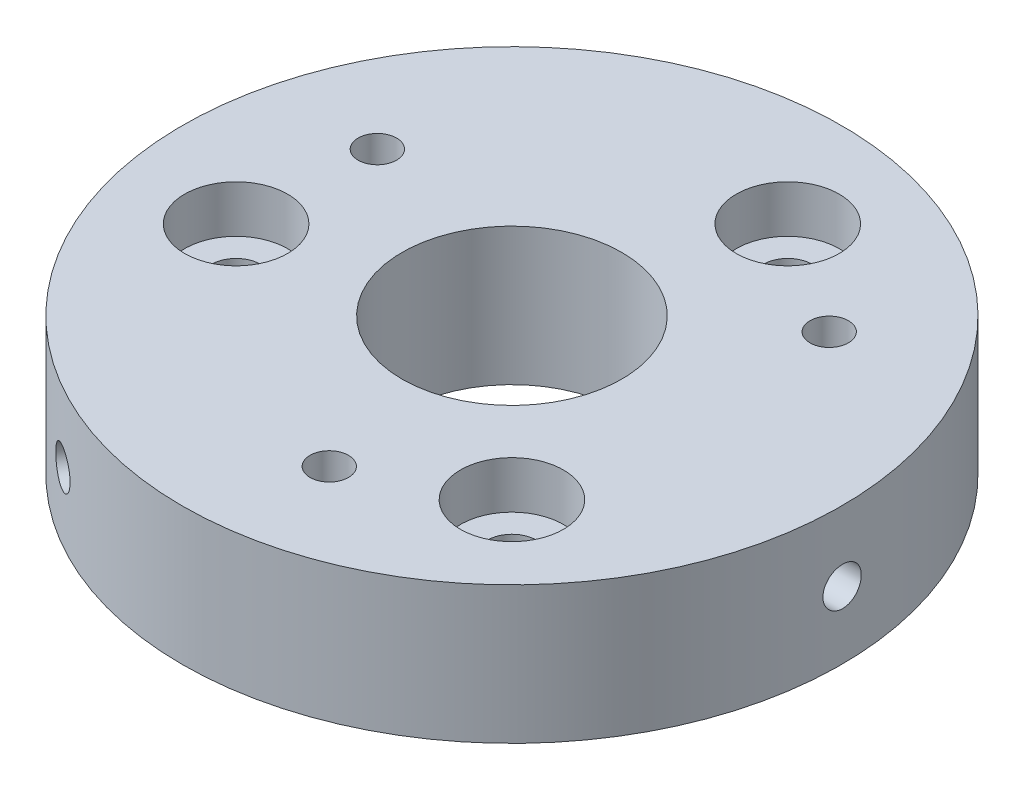
SolidWorks part; units mm, degrees
ref_plane "Front Plane" through (0, 0, 0) normal (0, 0, 1) x (1, 0, 0)
ref_plane "Top Plane" through (0, 0, 0) normal (0, 1, 0) x (1, 0, 0)
ref_plane "Right Plane" through (0, 0, 0) normal (1, 0, 0) x (0, 0, -1)
sketch "Sketch1" plane through (0, 0, 0) normal (0, 1, 0) x (1, 0, 0)
  circle A0 centre (0, 0) radius 15.24
  dimension "D1" = 30.48
extrude "Boss-Extrude1" add sketch "Sketch1" along normal blind 6.35
hole_wizard "CBORE for #2 Socket Head Cap Screw1" positions "Sketch3" profile "Sketch4" counterbore size "#2" standard "ANSI Inch" end condition through all
sketch "Sketch3" plane through (0, 6.35, 0) normal (0, 1, 0) x (1, 0, 0)
  line L3 (0, 0) -> (7.3638, -7.3638)
  point P0 (7.3638, -7.3638)
sketch "Sketch4" plane through (7.3638, 6.35, 7.3638) normal (1, 0, 0) x (0, 0, 1)
  line L0 (0, 0) -> (0, 6.35)
  line L1 (0, 6.35) -> (1.1303, 6.35)
  line L3 (1.1303, 6.35) -> (1.1303, 2.1844)
  line L4 (1.1303, 2.1844) -> (2.3812, 2.1844)
  line L5 (2.3812, 2.1844) -> (2.3812, 0)
  line L7 (2.3812, 0) -> (0, 0)
  line L11 (0, -6.35) -> (0, 107.95) construction
  dimension "Thru Hole Dia." = 2.2606
  dimension "Thru Hole Depth" = 6.35
  dimension "C'Bore Dia." = 4.7625
  dimension "C'Bore Depth" = 2.1844
pattern_circular "CirPattern1" count 3 over 360 about axis through (0, 0, 0) along (0, 1, 0) of "CBORE for #2 Socket Head Cap Screw1"
sketch "Sketch9" plane through (0, 6.35, 0) normal (0, 1, 0) x (1, 0, 0)
  line L0 (0, 0) -> (7.9776, 6.694)
  circle A0 centre (7.9776, 6.694) radius 1.4122
hole_wizard "Tap Drill for #2-56 Tap2" positions "3DSketch1" profile "Sketch10" hole size "#2-56" standard "ANSI Inch"
sketch3d "3DSketch1"
  point P0 (7.9776, 6.35, -6.694)
sketch "Sketch10" plane through (7.9776, 6.35, -6.694) normal (1, 0, 0) x (0, 0, 1)
  line L0 (0, 0) -> (0, 4.5982)
  line L1 (0, 4.5982) -> (0.889, 4.064)
  line L2 (0.889, 4.064) -> (0.889, 0)
  line L5 (0.889, 0) -> (0, 0)
  line L10 (0, 4.5982) -> (-0.889, 4.064) construction
  line L11 (0, -6.35) -> (0, 107.95) construction
  dimension "Hole Dia." = 1.778
  dimension "Hole Depth" = 4.064
  dimension "Drill Angle" = 118
pattern_circular "CirPattern2" count 3 every 120 about axis through (0, 0, 0) along (0, 1, 0) of "Tap Drill for #2-56 Tap2"
ref_plane "Plane1" [suppressed] through (0, 3.175, 0) normal (0, 1, 0) x (1, 0, 0)
sketch "Sketch11" [suppressed] plane through (0, 3.175, 0) normal (0, 1, 0) x (1, 0, 0)
  line L0 (0, 0) -> (-7.135, -12.0105)
  circle A0 centre (0, 0) radius 13.97 construction
ref_plane "Plane2" [suppressed] through (-7.135, 3.175, 12.0105) normal (-0.5107, 0, 0.8597) x (0.8597, 0, 0.5107)
hole_wizard "Tap Drill for #2-56 Tap1" positions "3DSketch3" profile "Sketch15" hole size "#2-56" standard "ANSI Inch"
sketch3d "3DSketch3"
  point P0 (-7.5736, 3.1056, 13.2249)
sketch "Sketch15" plane through (-7.5736, 3.1056, 13.2249) normal (0, 1, 0) x (0.8678, 0, 0.497)
  line L0 (0, 0) -> (0, 7.096)
  line L1 (0, 7.096) -> (0.889, 6.35)
  line L2 (0.889, 6.35) -> (0.889, 0)
  line L5 (0.889, 0) -> (0, 0)
  line L10 (0, 7.096) -> (-0.889, 6.35) construction
  line L11 (0, -6.35) -> (0, 107.95) construction
  dimension "Hole Dia." = 1.778
  dimension "Hole Depth" = 6.35
  dimension "Drill Angle" = 100
pattern_circular "CirPattern3" count 3 every 120 about axis through (0, 6.35, 0) along (0, -1, 0) of "Tap Drill for #2-56 Tap1"
sketch "Sketch16" plane through (0, 6.35, 0) normal (0, 1, 0) x (1, 0, 0)
  circle A0 centre (0, 0) radius 5.08
extrude "Cut-Extrude1" cut sketch "Sketch16" against normal blind 6.35
